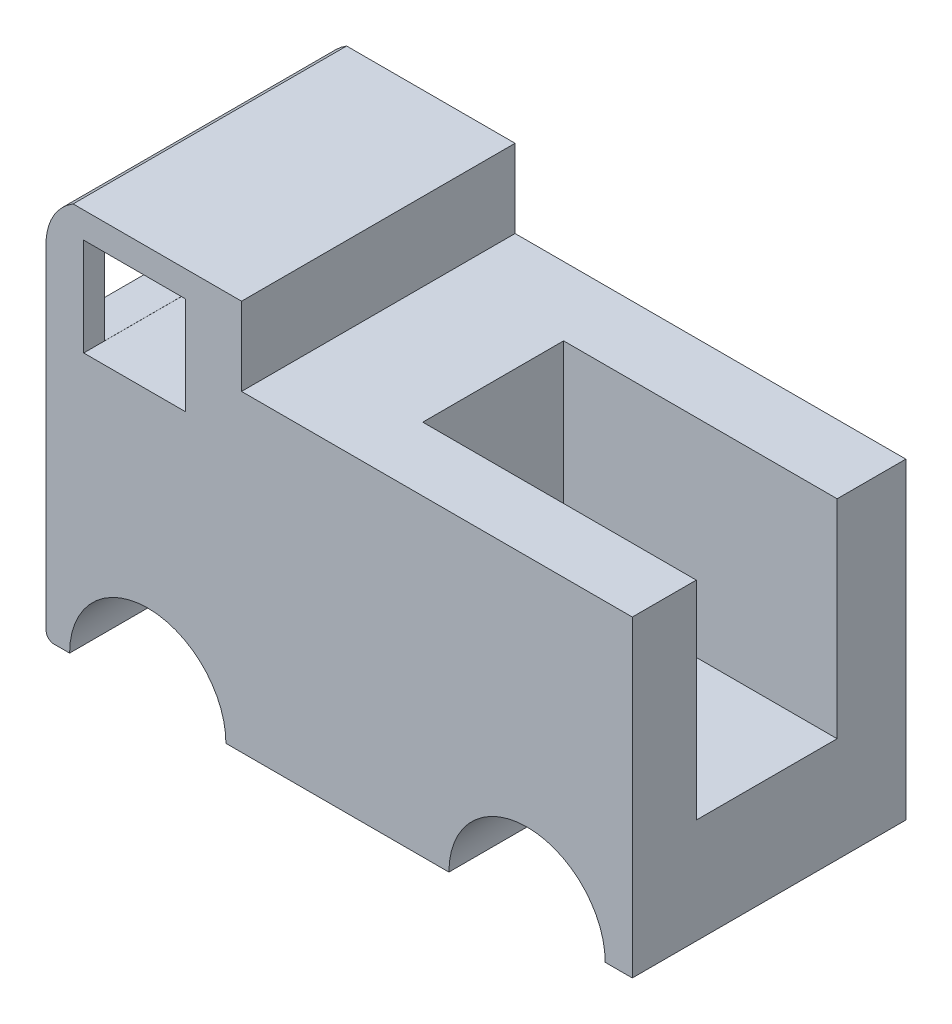
SolidWorks part; units mm, degrees
material "Alaşım Çelik (SS)"
ref_plane "Ön Düzlem" through (0, 0, 0) normal (0, 0, 1) x (1, 0, 0)
ref_plane "Üst Düzlem" through (0, 0, 0) normal (0, 1, 0) x (1, 0, 0)
ref_plane "Sağ Düzlem" through (0, 0, 0) normal (1, 0, 0) x (0, 0, -1)
sketch "Çizim1" plane through (0, 0, 0) normal (0, 0, 1) x (1, 0, 0)
  line L0 (250, -500) -> (250, 300)
  line L1 (-181.0952, 500) -> (250, 500)
  line L2 (-250, 386.7842) -> (-250, -480)
  line L3 (-230, -500) -> (-190, -500)
  line L4 (250, 500) -> (250, -500)
  line L5 (-227.4227, 454.8455) -> (250, -500) construction
  line L6 (-250, -500) -> (250, 500) construction
  line L7 (250, -500) -> (780.6729, -500)
  line L8 (250, 300) -> (1250, 300)
  line L9 (1250, -500) -> (1250, 300)
  line L10 (210, -500) -> (250, -500)
  line L11 (1180.6729, -500) -> (1250, -500)
  arc A1 (-181.0952, 500) -> (-250, 386.7842) centre (-106.2604, 376.8783) ccw
  arc A2 (-250, -480) -> (-230, -500) centre (-230, -480) ccw
  arc A3 (210, -500) -> (-190, -500) centre (10, -500) ccw
  arc A4 (1180.6729, -500) -> (780.6729, -500) centre (980.6729, -500) ccw
  point P0 (0, 0)
  dimension "D3" = 500
  dimension "D1" = 20
  dimension "D4" = 1000
  dimension "D5" = 800
extrude "Yükseklik-Ekstrüzyon1" add sketch "Çizim1" against normal blind 700 contours A3 L10 L0 L4 L1 A1 L2 A2 L3 | A4 L11 L9 L8 L0 L7
sketch "Çizim2" plane through (1250, 0, 0) normal (1, 0, 0) x (0, 0, -1)
  line L0 (163.7453, 300) -> (524.1951, 300)
  line L1 (163.7453, 300) -> (163.7453, -231.8135)
  line L2 (524.1951, 300) -> (524.1951, -231.8135)
  line L3 (163.7453, -231.8135) -> (524.1951, -231.8135)
  line L4 (700, 300) -> (0, 300) construction
extrude "Kes-Ekstrüzyon1" cut sketch "Çizim2" against normal blind 700
sketch "Çizim3" plane through (0, 0, -700) normal (0, 0, -1) x (-1, 0, 0)
  line L0 (-107.0561, 433.3255) -> (153.8711, 433.3255)
  line L1 (-107.0561, 433.3255) -> (-107.0561, 183.2703)
  line L2 (153.8711, 433.3255) -> (153.8711, 183.2703)
  line L3 (-107.0561, 183.2703) -> (153.8711, 183.2703)
extrude "Kes-Ekstrüzyon2" cut sketch "Çizim3" against normal blind 700
sketch "Çizim4" plane through (-250, 0, 0) normal (-1, 0, 0) x (0, 0, 1)
  line L0 (-645.5359, 386.7842) -> (-645.5359, 183.5263)
  line L1 (-645.5359, 386.7842) -> (-53.0282, 386.7842)
  line L2 (-645.5359, 183.5263) -> (-53.0282, 183.5263)
  line L3 (-53.0282, 386.7842) -> (-53.0282, 183.5263)
extrude "Kes-Ekstrüzyon3" cut sketch "Çizim4" against normal blind 100
